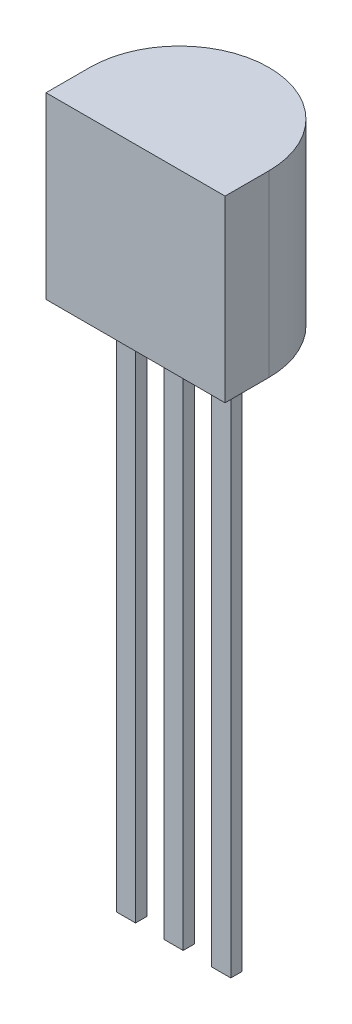
SolidWorks part; units mm, degrees
ref_plane "前视基准面" through (0, 0, 0) normal (0, 0, 1) x (1, 0, 0)
ref_plane "上视基准面" through (0, 0, 0) normal (0, 1, 0) x (1, 0, 0)
ref_plane "右视基准面" through (0, 0, 0) normal (1, 0, 0) x (0, 0, -1)
sketch "草图1" plane through (0, 0, 0) normal (0, 1, 0) x (1, 0, 0)
  line L0 (-2.35, 0) -> (2.35, 0)
  line L1 (-2.35, 0) -> (-2.35, 1.15)
  line L2 (0, -9.9847) -> (0, 31.9184) construction
  line L3 (2.35, 0) -> (2.35, 1.15)
  line L4 (2.5443, 3.5) -> (-3.4027, 3.5) construction
  line L5 (-4.1666, 1.15) -> (5.1384, 1.15) construction
  arc A0 (2.35, 1.15) -> (-2.35, 1.15) centre (0, 1.15) ccw
  dimension "D1" = 4.7
  dimension "D2" = 3.5
extrude "凸台-拉伸1" add sketch "草图1" along normal blind 4.7
sketch "草图2" plane through (0, 0, 0) normal (0, -1, 0) x (1, 0, 0)
  line L0 (-2.8551, -1.15) -> (2.9269, -1.15) construction
  line L1 (0, 0.5568) -> (0, -3.9133) construction
  line L2 (1, -1) -> (1.5, -1)
  line L3 (-0.25, -1) -> (0.25, -1)
  line L4 (-0.25, -1) -> (-0.25, -1.3)
  line L5 (-0.25, -1.3) -> (0.25, -1.3)
  line L6 (0.25, -1) -> (0.25, -1.3)
  line L7 (1, -1) -> (1, -1.3)
  line L8 (1, -1.3) -> (1.5, -1.3)
  line L9 (1.5, -1) -> (1.5, -1.3)
  line L10 (-1.5, -1) -> (-1.5, -1.3)
  line L11 (-1, -1.3) -> (-1.5, -1.3)
  line L12 (-1, -1) -> (-1, -1.3)
  line L13 (-1, -1) -> (-1.5, -1)
  dimension "D1" = 0.5
  dimension "D2" = 0.3
  dimension "D3" = 2
extrude "凸台-拉伸2" add sketch "草图2" along normal blind 14
